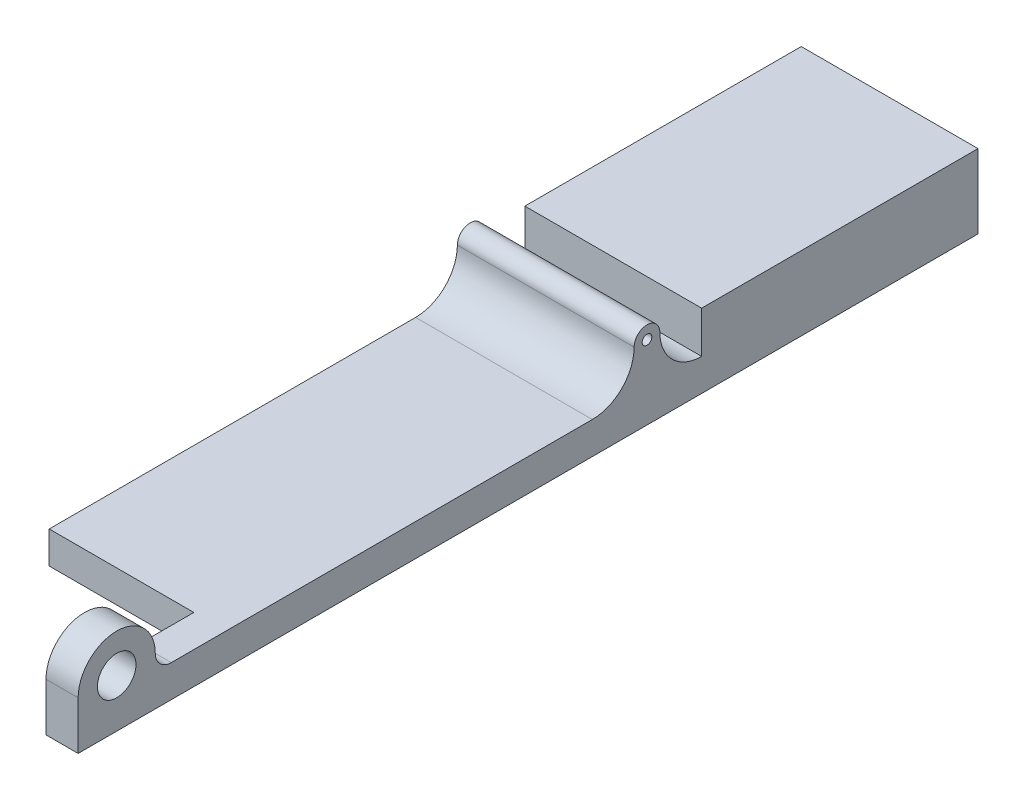
SolidWorks part; units mm, degrees
ref_plane "Front Plane" through (0, 0, 0) normal (0, 0, 1) x (1, 0, 0)
ref_plane "Top Plane" through (0, 0, 0) normal (0, 1, 0) x (1, 0, 0)
ref_plane "Right Plane" through (0, 0, 0) normal (1, 0, 0) x (0, 0, -1)
sketch "Sketch1" plane through (0, 0, 0) normal (1, 0, 0) x (0, 0, -1)
  line L12 (3, 15) -> (3, 0)
  line L13 (3, 0) -> (283, 0)
  line L14 (32, 10) -> (163, 10)
  line L15 (283, 0) -> (283, 23)
  line L16 (283, 23) -> (197, 23)
  line L17 (197, 23) -> (197, 10)
  circle A0 centre (15, 15) radius 6
  circle A1 centre (180, 23) radius 1.5
  arc A2 (15, 27) -> (27, 15) centre (15, 15) cw
  arc A3 (15, 27) -> (3, 15) centre (15, 15) ccw
  arc A4 (184, 23) -> (176, 23) centre (180, 23) ccw
  arc A5 (27, 15) -> (32, 10) centre (32, 15) ccw
  arc A6 (176, 23) -> (163, 10) centre (163, 23) cw
  arc A7 (184, 23) -> (197, 10) centre (197, 23) ccw
  point P21 (198.0845, 10)
  dimension "D3" = 12
  dimension "D9" = 3
  dimension "D2" = 280
  dimension "D5" = 12
  dimension "D6" = 5
  dimension "D8" = 10
  dimension "D13" = 13
  dimension "D14" = 4
  dimension "D4" = 15
  dimension "D7" = 12
  dimension "D10" = 165
  dimension "D11" = 8
  dimension "D12" = 131
extrude "Boss-Extrude1" add sketch "Sketch1" along normal blind 55
sketch "Sketch2" plane through (0, 0, 0) normal (0, -1, 0) x (1, 0, 0)
  line L1 (0, -3) -> (45, -3)
  line L2 (0, -3) -> (0, -49)
  line L3 (0, -49) -> (45, -49)
  line L4 (45, -3) -> (45, -49)
  dimension "D1" = 45
  dimension "D2" = 46
extrude "Cut-Extrude1" cut sketch "Sketch2" against normal through all
